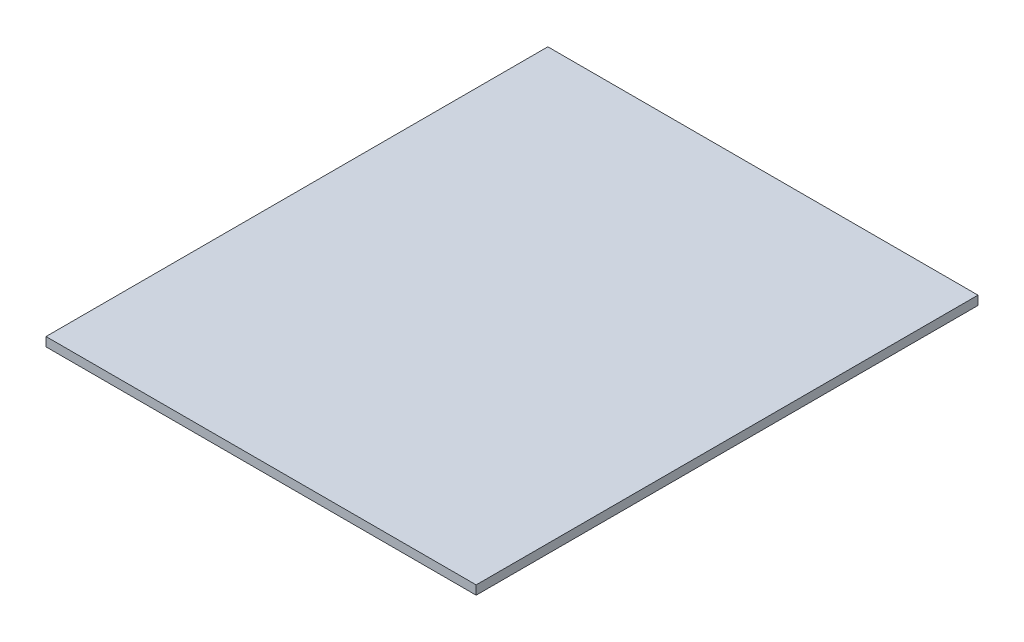
SolidWorks part; units mm, degrees
ref_plane "Front Plane" through (0, 0, 0) normal (0, 0, 1) x (1, 0, 0)
ref_plane "Top Plane" through (0, 0, 0) normal (0, 1, 0) x (1, 0, 0)
ref_plane "Right Plane" through (0, 0, 0) normal (1, 0, 0) x (0, 0, -1)
sketch "Sketch1" plane through (0, 0, 0) normal (0, 1, 0) x (1, 0, 0)
  line L1 (0, 0) -> (152.4, 0)
  line L2 (0, 0) -> (0, 177.8)
  line L3 (0, 177.8) -> (152.4, 177.8)
  line L4 (152.4, 0) -> (152.4, 177.8)
  dimension "D1" = 177.8
  dimension "D2" = 152.4
extrude "Boss-Extrude1" add sketch "Sketch1" along normal blind 3.175
